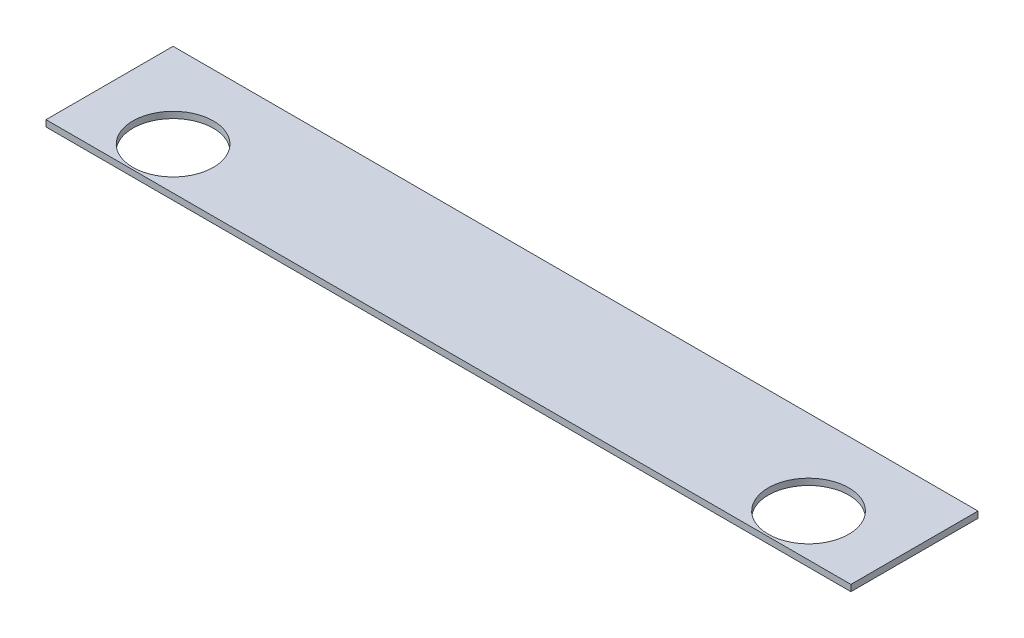
SolidWorks part; units mm, degrees
ref_plane "Front Plane" through (0, 0, 0) normal (0, 0, 1) x (1, 0, 0)
ref_plane "Top Plane" through (0, 0, 0) normal (0, 1, 0) x (1, 0, 0)
ref_plane "Right Plane" through (0, 0, 0) normal (1, 0, 0) x (0, 0, -1)
sketch "Sketch1" plane through (0, 0, 0) normal (0, 1, 0) x (1, 0, 0)
  line L1 (-19, -3) -> (19, -3)
  line L2 (-19, -3) -> (-19, 3)
  line L3 (-19, 3) -> (19, 3)
  line L4 (19, -3) -> (19, 3)
  line L5 (-19, -3) -> (19, 3) construction
  line L6 (-19, 3) -> (19, -3) construction
  circle A0 centre (-15, -1) radius 1.9
  circle A1 centre (15, -1) radius 1.9
  point P0 (0, 0)
  dimension "4" = 3.8
  dimension "D1" = 38
  dimension "D2" = 30
  dimension "D3" = 15
  dimension "D4" = 6
  dimension "D5" = 4
extrude "Boss-Extrude2" add sketch "Sketch1" along normal blind 0.3
equation "\"D3@Sketch1\"=\"D2@Sketch1\"/2"
